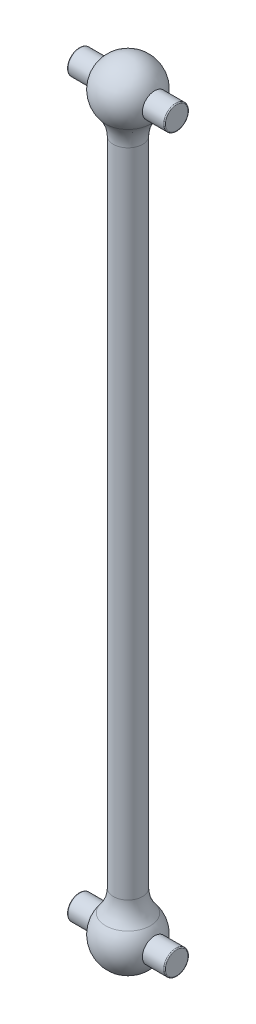
SolidWorks part; units mm, degrees
ref_plane "Front Plane" through (0, 0, 0) normal (0, 0, 1) x (1, 0, 0)
ref_plane "Top Plane" through (0, 0, 0) normal (0, 1, 0) x (1, 0, 0)
ref_plane "Right Plane" through (0, 0, 0) normal (1, 0, 0) x (0, 0, -1)
sketch "Sketch1" plane through (0, 0, 0) normal (0, 1, 0) x (1, 0, 0)
  circle A0 centre (0, 0) radius 1.905
  dimension "D1" = 3.81
extrude "Boss-Extrude1" add sketch "Sketch1" along normal blind 47.625
sketch "Sketch2" plane through (0, 0, 0) normal (0, 0, 1) x (1, 0, 0)
  line L0 (1.905, 47.625) -> (-1.905, 47.625) construction
  line L1 (0, 51.435) -> (0, 47.625) construction
  line L2 (0, 47.625) -> (2.9186, 45.176) construction
  line L3 (1.905, 0) -> (1.905, 47.625) construction
  line L4 (1.905, 42.3911) -> (0, 42.3911)
  line L5 (0, 51.435) -> (0, 42.3911)
  arc A0 (0, 51.435) -> (2.9186, 45.176) centre (0, 47.625) cw
  arc A1 (2.9186, 45.176) -> (1.905, 42.3911) centre (6.2376, 42.3911) ccw
  dimension "D1" = 3.81
  dimension "D2" = 130
revolve "Revolve2" add sketch "Sketch2" angle 360 about L5
sketch "Sketch3" plane through (0, 0, 0) normal (1, 0, 0) x (0, 0, -1)
  circle A0 centre (0, 47.625) radius 1.5875
  arc A1 (2.9186, 45.176) -> (-2.9186, 45.176) centre (0, 47.625) ccw construction
  dimension "D1" = 3.175
extrude "Boss-Extrude2" add sketch "Sketch3" along normal mid plane 12.7
fillet "Fillet1" radius 0.127 2 edges at (-6.35, 47.625, -1.5875) (6.35, 47.625, -1.5875)
mirror "Mirror1" of "Fillet1", "Boss-Extrude2", "Revolve2", "Boss-Extrude1"
equation "\"x\"= \"l\" / 2"
equation "\"D1@Boss-Extrude1\"=\"x\""
equation "\"l\"= 3.75'Length of Rod"
